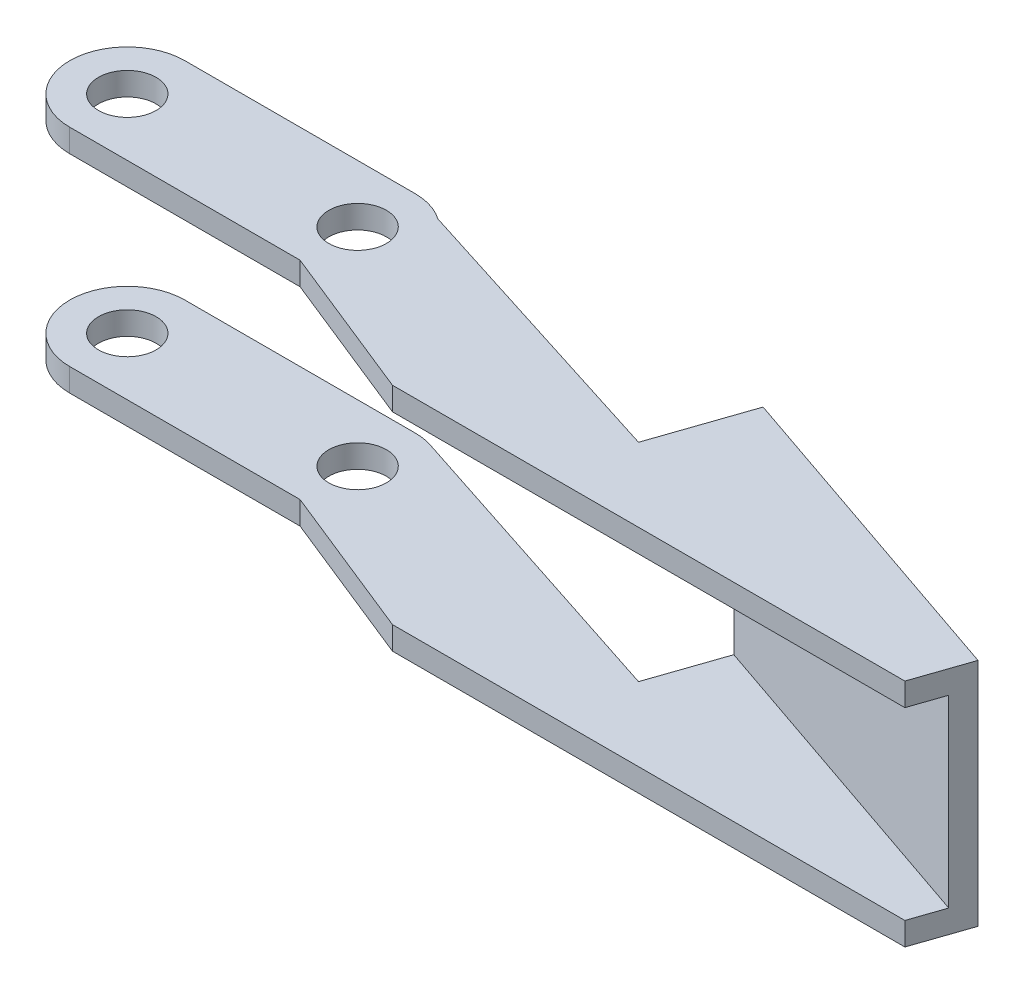
SolidWorks part; units mm, degrees
ref_plane "Front Plane" through (0, 0, 0) normal (0, 0, 1) x (1, 0, 0)
ref_plane "Top Plane" through (0, 0, 0) normal (0, 1, 0) x (1, 0, 0)
ref_plane "Right Plane" through (0, 0, 0) normal (1, 0, 0) x (0, 0, -1)
sketch "Sketch1" plane through (0, 0, 0) normal (0, 1, 0) x (1, 0, 0)
  line L0 (0, 0) -> (20, 0) construction
  line L1 (0, 5) -> (20, 5)
  line L2 (0, -5) -> (20, -5)
  arc A0 (0, 5) -> (0, -5) centre (0, 0) ccw
  arc A1 (20, -5) -> (20, 5) centre (20, 0) ccw
  circle A2 centre (0, 0) radius 2.5
  circle A3 centre (20, 0) radius 2.5
  point P3 (10, 0)
  dimension "D3" = 5
  dimension "D4" = 5
  dimension "D1" = 20
  dimension "D2" = 10
extrude "Boss-Extrude1" add sketch "Sketch1" along normal blind 2
sketch "Sketch2" plane through (0, 2, 0) normal (0, 1, 0) x (1, 0, 0)
  line L0 (26, 5) -> (63.1764, -9.942) construction
  line L1 (20, -5) -> (59.107, -20.718) construction
  line L2 (9.344, 5) -> (69.6955, 5) construction
  line L3 (20, 5) -> (0, 5) construction
  line L4 (9.344, -5) -> (50.8804, -5) construction
  line L5 (0, -5) -> (20, -5) construction
  line L6 (48.3923, 5) -> (48.3923, -5) construction
  line L7 (48.3923, 5) -> (111.444, -16.5904) construction
sketch "Sketch3" plane through (0, 2, 0) normal (0, 1, 0) x (1, 0, 0)
  line L0 (20, 5) -> (48.3923, -4)
  line L1 (48.3923, 5) -> (48.3923, -5) construction
  line L2 (26, 5) -> (63.1764, -9.942) construction
  line L3 (20, 5) -> (24.3174, 2.5219)
  line L4 (51.1507, 4.0555) -> (79.5329, -5.6633)
  line L5 (48.3923, 5) -> (111.444, -16.5904) construction
  line L6 (24.3174, 2.5219) -> (20, -5)
  line L7 (77.9131, -10.3936) -> (33.4195, -10.3936)
  line L8 (20, -5) -> (59.107, -20.718) construction
  line L9 (33.4195, -10.3936) -> (20, -5)
  line L10 (9.344, 5) -> (69.6955, 5) construction
  line L11 (48.3923, -4) -> (51.1507, 4.0555)
  line L12 (79.5329, -5.6633) -> (77.9131, -10.3936)
  arc A0 (20, -5) -> (20, 5) centre (20, 0) ccw construction
  dimension "D1" = 5
  dimension "D2" = 30
extrude "Boss-Extrude2" add sketch "Sketch3" against normal blind 2
sketch "Sketch4" plane through (0, 0, 0) normal (0, -1, 0) x (1, 0, 0)
  line L0 (51.1507, -4.0555) -> (79.5329, 5.6633)
  line L1 (51.1507, -4.0555) -> (50.5028, -2.1633)
  line L2 (79.5329, 5.6633) -> (78.885, 7.5554)
  line L3 (50.5028, -2.1633) -> (78.885, 7.5554)
  dimension "D1" = 2
extrude "Boss-Extrude3" add sketch "Sketch4" along normal blind 16
sketch "Sketch5" plane through (0, -16, 0) normal (0, -1, 0) x (1, 0, 0)
  line L0 (51.1507, -4.0555) -> (48.3923, 4)
  line L1 (48.3923, 4) -> (21.5108, -4.7663)
  line L2 (0, 0) -> (20, 0) construction
  line L3 (0, 5) -> (20, 5)
  line L4 (0, -5) -> (20, -5)
  line L5 (51.1507, -4.0555) -> (79.5329, 5.6633)
  line L6 (79.5329, 5.6633) -> (77.9131, 10.3936)
  line L7 (77.9131, 10.3936) -> (33.4195, 10.3936)
  line L8 (33.4195, 10.3936) -> (20, 5)
  arc A0 (20, -5) -> (22.8804, -4.0869) centre (20, 0) ccw construction
  arc A1 (0, 5) -> (0, -5) centre (0, 0) ccw
  arc A2 (20, -5) -> (21.5894, -4.7406) centre (20, 0) ccw
  circle A3 centre (0, 0) radius 2.5
  circle A4 centre (20, 0) radius 2.5
  point P12 (13, 0)
  dimension "D1" = 10
extrude "Boss-Extrude4" add sketch "Sketch5" along normal blind 2
